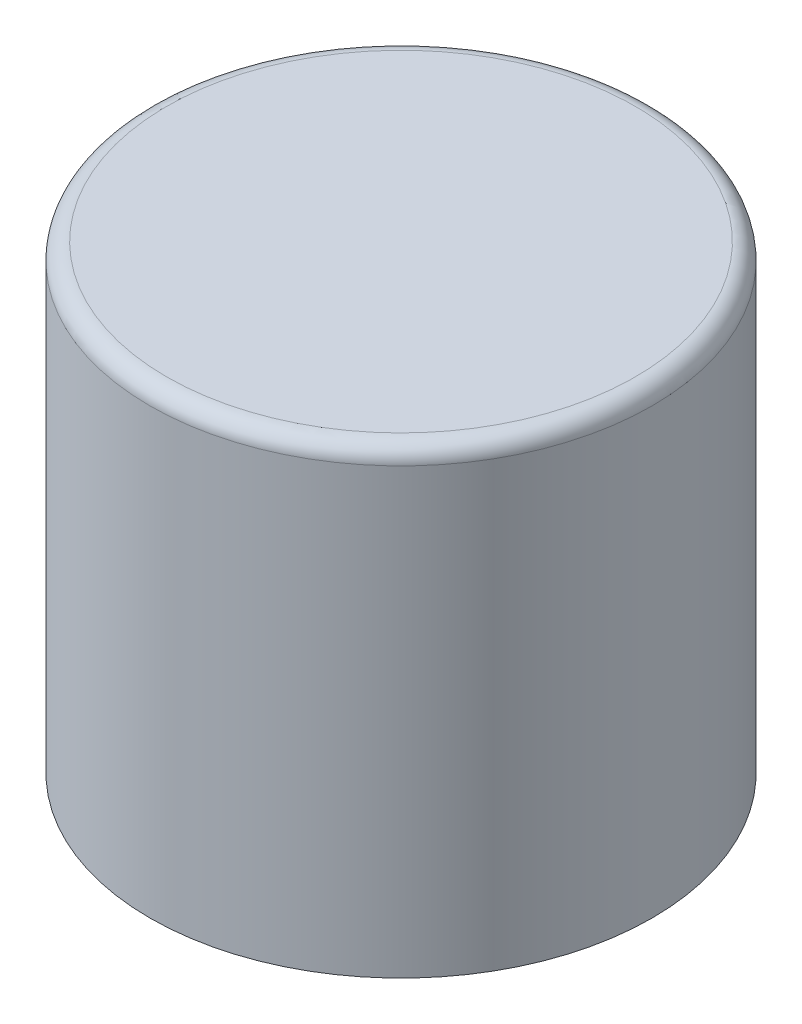
SolidWorks part; units mm, degrees
ref_plane "Front" through (0, 0, 0) normal (0, 0, 1) x (1, 0, 0)
ref_plane "Top" through (0, 0, 0) normal (0, 1, 0) x (1, 0, 0)
ref_plane "Right" through (0, 0, 0) normal (1, 0, 0) x (0, 0, -1)
ref_plane "Plane1" through (0, 0, 0) normal (0, 0, -1) x (-1, 0, 0)
sketch "Sketch1" plane through (0, 0, 0) normal (0, 0, -1) x (-1, 0, 0)
  line L0 (-3, 0) -> (0, 0)
  line L1 (0, 0) -> (0, 5.5)
  line L2 (0, 5.5) -> (-3, 5.5)
  line L3 (-3, 5.5) -> (-3, 0)
  line L4 (0, 0) -> (0, 5.5) construction
revolve "Revolve1" add sketch "Sketch1" angle 360 about L4
sketch "Sketch2" plane through (0, 0, 0) normal (0, -1, 0) x (1, 0, 0)
  line L0 (1.25, 1.25) -> (-1.25, 1.25)
  line L1 (-1.25, 1.25) -> (-1.25, -1.25)
  line L2 (-1.25, -1.25) -> (1.25, -1.25)
  line L3 (1.25, -1.25) -> (1.25, 1.25)
extrude "Cut-Extrude1" cut sketch "Sketch2" against normal blind 2.8
fillet "Fillet1" radius 0.2 1 edges at (0, 5.5, 3)
